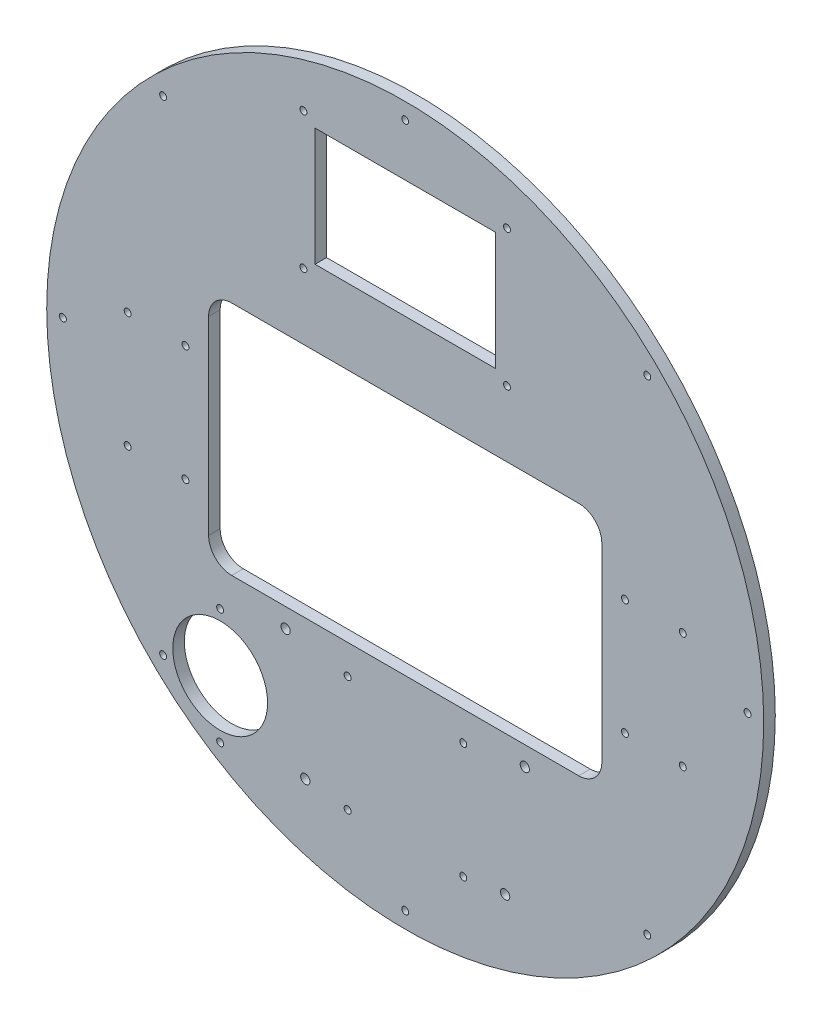
SolidWorks part; units mm, degrees
ref_plane "前视基准面" through (0, 0, 0) normal (0, 0, 1) x (1, 0, 0)
ref_plane "上视基准面" through (0, 0, 0) normal (0, 1, 0) x (1, 0, 0)
ref_plane "右视基准面" through (0, 0, 0) normal (1, 0, 0) x (0, 0, -1)
sketch "草图1" plane through (0, 0, 0) normal (0, 0, 1) x (1, 0, 0)
  line L0 (0, 203.2075) -> (0, -205.478) construction
  line L1 (-179.3675, 0) -> (188.4494, 0) construction
  circle A0 centre (0, 0) radius 155
  dimension "D1" = 310
extrude "凸台-拉伸1" add sketch "草图1" along normal blind 5
sketch "草图13" plane through (0, 0, 5) normal (0, 0, 1) x (1, 0, 0)
  line L0 (-161.956, 0) -> (175.2877, 0) construction
  line L1 (0, 166.6468) -> (0, -178.991) construction
  line L2 (-71.5, -10) -> (71.5, -10) construction
  line L3 (-71.5, 20) -> (71.5, 20)
  line L4 (-71.5, 20) -> (-71.5, -40)
  line L5 (-71.5, -40) -> (71.5, -40)
  line L6 (71.5, 20) -> (71.5, -40)
  dimension "D1" = 143
  dimension "D2" = 60
  dimension "D3" = 71.5
  dimension "D4" = 10
sketch "草图14" plane through (0, 0, 5) normal (0, 0, 1) x (1, 0, 0)
  line L0 (0, 166.6468) -> (0, -178.991) construction
  line L1 (-85, -40) -> (85, -40) construction
  line L2 (-85, -40) -> (-85, -56) construction
  line L3 (-85, -56) -> (85, -56) construction
  line L4 (85, -40) -> (85, -56) construction
  line L5 (-85, -48) -> (85, -48) construction
  line L6 (0, -40) -> (0, -56) construction
  line L7 (-71.5, -10) -> (71.5, -10) construction
  circle A0 centre (-80, -45) radius 1.5
  circle A1 centre (-80, -51) radius 1.5
  circle A2 centre (80, -51) radius 1.5
  circle A3 centre (80, -45) radius 1.5
  dimension "D5" = 3
  dimension "D1" = 16
  dimension "D2" = 170
  dimension "D3" = 85
  dimension "D4" = 30
  dimension "D6" = 5
  dimension "D7" = 5
sketch "草图16" plane through (0, 0, 5) normal (0, 0, 1) x (1, 0, 0)
  line L0 (0, 181.7623) -> (0, -199.6765) construction
  line L1 (-196.5571, 0) -> (202.1518, 0) construction
  circle A0 centre (0, 148) radius 1.5
  circle A1 centre (0, 0) radius 155 construction
  circle A2 centre (104.6518, 104.6518) radius 1.5
  circle A3 centre (148, 0) radius 1.5
  circle A4 centre (104.6518, -104.6518) radius 1.5
  circle A5 centre (0, -148) radius 1.5
  circle A6 centre (-104.6518, -104.6518) radius 1.5
  circle A7 centre (-148, 0) radius 1.5
  circle A8 centre (-104.6518, 104.6518) radius 1.5
  point P26 (0, 0)
  dimension "D1" = 3
  dimension "D2" = 148
  dimension "D3" = 8
extrude "切除-拉伸15" cut sketch "草图16" against normal through all
sketch "草图17" plane through (0, 0, 5) normal (0, 0, 1) x (1, 0, 0)
  line L0 (0, 178.4383) -> (0, -183.7647) construction
  line L1 (-199.1253, 0) -> (199.2323, 0) construction
  line L2 (-80, -75) -> (-80, -125) construction
  circle A0 centre (-80, -75) radius 1.5
  circle A1 centre (-80, -125) radius 1.5
  circle A2 centre (-80, -100) radius 20.5
  dimension "D1" = 3
  dimension "D2" = 3
  dimension "D4" = 41
  dimension "D6" = 100
  dimension "D3" = 50
  dimension "D5" = 80
extrude "切除-拉伸16" cut sketch "草图17" against normal through all
sketch "草图19" plane through (0, 0, 5) normal (0, 0, 1) x (1, 0, 0)
  line L2 (40, -59.4824) -> (40, -101.7) construction
  line L3 (-40, -97.7) -> (-40, -59.4824) construction
  line L4 (-44, -97.7) -> (-44, -59.4824)
  line L5 (44, -59.4824) -> (44, -101.8952)
  line L6 (-44, -97.7) -> (-44, -59.4824) construction
  line L7 (44, -59.4824) -> (44, -101.8952) construction
  line L8 (-40, -59.4824) -> (40, -59.4824) construction
  line L9 (-56, -97.7) -> (-56, -59.4824) construction
  line L10 (56, -59.4824) -> (56, -102.4329) construction
  line L11 (-44, -59.4824) -> (-56, -59.4824) construction
  line L12 (56, -59.4824) -> (44, -59.4824) construction
  line L13 (0.1, -97.7) -> (62.9387, -97.7) construction
  line L14 (0.1, -97.7) -> (0.1, -48.6409) construction
  arc A1 (-40, -97.7) -> (40, -101.7) centre (0.1, -97.7) ccw construction
  arc A2 (-44, -97.7) -> (44, -101.8952) centre (0.1, -97.7) ccw
  arc A3 (-44, -97.7) -> (44, -101.8952) centre (0.1, -97.7) ccw construction
  arc A4 (-56, -97.7) -> (56, -102.4329) centre (0.1, -97.7) ccw construction
  circle A5 centre (51.7, -68.3) radius 2
  circle A6 centre (43.2, -120.3) radius 2
  circle A7 centre (-43.2, -120.3) radius 2
  circle A8 centre (-51.7, -68.3) radius 2
  circle A9 centre (25.1, -72.7) radius 1.5
  circle A10 centre (25.1, -122.7) radius 1.5
  circle A11 centre (-24.9, -122.7) radius 1.5
  circle A12 centre (-24.9, -72.7) radius 1.5
  dimension "D4" = 3
  dimension "D5" = 25
  dimension "D6" = 25
  dimension "D1" = 1
  dimension "D2" = 4
  dimension "D3" = 12
extrude "切除-拉伸17" cut sketch "草图19" against normal through all
sketch "草图20" plane through (0, 0, 5) normal (0, 0, 1) x (1, 0, 0)
  line L0 (0, 173.8253) -> (0, -187.4094) construction
  line L1 (-197.1682, 0) -> (206.8795, 0) construction
  line L3 (-75, 42) -> (75, 42)
  line L4 (-85, 32) -> (-85, -50)
  line L5 (-75, -60) -> (75, -60)
  line L6 (85, 32) -> (85, -50)
  arc A0 (75, 42) -> (85, 32) centre (75, 32) cw
  arc A1 (75, -60) -> (85, -50) centre (75, -50) ccw
  arc A2 (-85, -50) -> (-75, -60) centre (-75, -50) ccw
  arc A3 (-75, 42) -> (-85, 32) centre (-75, 32) ccw
  dimension "D5" = 10
  dimension "D1" = 42
  dimension "D2" = 60
  dimension "D3" = 85
  dimension "D4" = 85
extrude "切除-拉伸18" cut sketch "草图20" against normal through all
sketch "草图21" plane through (0, 0, 5) normal (0, 0, 1) x (1, 0, 0)
  line L0 (-85, -9) -> (85, -9) construction
  line L1 (-85, 32) -> (-85, -50) construction
  line L2 (85, -50) -> (85, 32) construction
  line L3 (85, 16) -> (125, 16) construction
  line L4 (65, 11) -> (125, 11) construction
  line L5 (65, 11) -> (65, -29) construction
  line L6 (65, -29) -> (125, -29) construction
  line L7 (125, 11) -> (125, -29) construction
  line L8 (125, 11) -> (85, 11) construction
  line L9 (125, 11) -> (125, 21) construction
  line L10 (125, 21) -> (85, 21) construction
  line L11 (85, 11) -> (85, 21) construction
  line L12 (125, -29) -> (85, -29) construction
  line L13 (125, -29) -> (125, -39) construction
  line L14 (125, -39) -> (85, -39) construction
  line L15 (85, -29) -> (85, -39) construction
  line L16 (105, 21) -> (105, 11) construction
  line L17 (0, 35.904) -> (0, -53.1679) construction
  circle A0 centre (95, 16) radius 1.5
  circle A1 centre (120, 16) radius 1.5
  circle A2 centre (120, -34) radius 1.5
  circle A3 centre (95, -34) radius 1.5
  circle A4 centre (-120, -34) radius 1.5
  circle A5 centre (-95, -34) radius 1.5
  circle A6 centre (-120, 16) radius 1.5
  circle A7 centre (-95, 16) radius 1.5
  dimension "D7" = 3
  dimension "D8" = 3
  dimension "D10" = 20
  dimension "D1" = 20
  dimension "D2" = 20
  dimension "D3" = 20
  dimension "D4" = 40
  dimension "D5" = 10
  dimension "D6" = 10
  dimension "D9" = 25
extrude "切除-拉伸19" cut sketch "草图21" against normal through all
sketch "草图22" plane through (0, 0, 5) normal (0, 0, 1) x (1, 0, 0)
  line L0 (0, 175.8606) -> (0, -67.3478) construction
  line L1 (-39, 100) -> (39, 100) construction
  line L2 (-39, 125.5) -> (39, 125.5)
  line L3 (-39, 125.5) -> (-39, 74.5)
  line L4 (-39, 74.5) -> (39, 74.5)
  line L5 (39, 125.5) -> (39, 74.5)
  line L6 (-44, 129.5) -> (44, 129.5) construction
  line L7 (-44, 129.5) -> (-44, 70.5) construction
  line L8 (-44, 70.5) -> (44, 70.5) construction
  line L9 (44, 129.5) -> (44, 70.5) construction
  circle A0 centre (-44, 129.5) radius 1.5
  circle A1 centre (44, 129.5) radius 1.5
  circle A2 centre (44, 70.5) radius 1.5
  circle A3 centre (-44, 70.5) radius 1.5
  dimension "D9" = 3
  dimension "D10" = 3
  dimension "D11" = 3
  dimension "D12" = 3
  dimension "D1" = 78
  dimension "D2" = 78
  dimension "D3" = 51
  dimension "D4" = 59
  dimension "D5" = 88
  dimension "D6" = 44
  dimension "D7" = 29.5
  dimension "D8" = 100
extrude "切除-拉伸20" cut sketch "草图22" against normal through all
